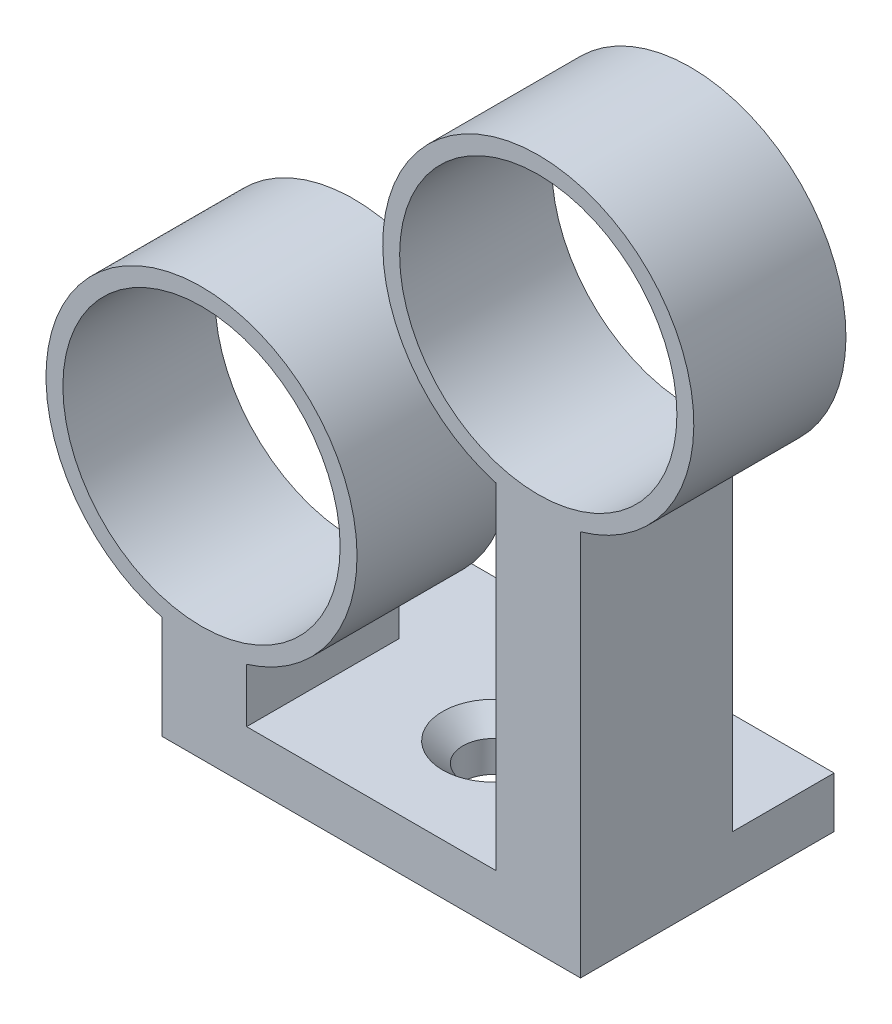
SolidWorks part; units mm, degrees
ref_plane "Alzado" through (0, 0, 0) normal (0, 0, 1) x (1, 0, 0)
ref_plane "Planta" through (0, 0, 0) normal (0, 1, 0) x (1, 0, 0)
ref_plane "Vista lateral" through (0, 0, 0) normal (1, 0, 0) x (0, 0, -1)
sketch "Sketch1" plane through (0, 0, 0) normal (0, 0, 1) x (1, 0, 0)
  line L0 (0.295, 24.8228) -> (61.4006, 24.8228) construction
  circle A0 centre (2.6252, 39.8228) radius 8.2
  circle A1 centre (22.5445, 56.5328) radius 8.2
  circle A3 centre (22.5445, 56.5328) radius 9.2
  circle A7 centre (2.6252, 39.8228) radius 9.2
  dimension "D3" = 16.4
  dimension "D5" = 16.4
  dimension "D4" = 18.4
  dimension "D1" = 18.4
  dimension "D6" = 26
  dimension "D7" = 31.71
extrude "Boss-Extrude1" add sketch "Sketch1" along normal blind 9
sketch "Sketch2" plane through (0, 0, 0) normal (0, 0, 1) x (1, 0, 0)
  line L1 (0.295, 24.8228) -> (5.295, 24.8228)
  line L2 (0.295, 24.8228) -> (0.295, 30.9228)
  line L4 (5.295, 24.8228) -> (5.295, 31.0187)
  line L7 (20.0445, 47.7228) -> (20.0445, 24.8228)
  line L8 (20.0445, 24.8228) -> (25.0445, 24.8228)
  line L9 (25.0445, 47.7228) -> (25.0445, 24.8228)
  arc A6 (20.0445, 47.7228) -> (25.0445, 47.7228) centre (22.5445, 55.5406) ccw
  arc A7 (0.295, 30.9228) -> (5.295, 31.0187) centre (2.6252, 39.8228) ccw
  dimension "D1" = 5
  dimension "D2" = 6.1
  dimension "D8" = 5
  dimension "D9" = 22.9
  dimension "D10" = 22.9
extrude "Boss-Extrude2" add sketch "Sketch2" along normal blind 9
sketch "Sketch3" plane through (0, 24.8228, 0) normal (0, -1, 0) x (1, 0, 0)
  line L1 (0.295, 9) -> (25.0445, 9)
  line L2 (0.295, 9) -> (0.295, -6)
  line L3 (0.295, -6) -> (25.0445, -6)
  line L4 (25.0445, 9) -> (25.0445, -6)
  dimension "D1" = 24.7495
  dimension "D2" = 15
extrude "Boss-Extrude3" add sketch "Sketch3" against normal blind 3
hole_wizard "Avellanado para tornillo con cabeza avellanada en cruz de M31" positions "3DSketch2" profile "Sketch5" countersink size "M3" standard "AS"
sketch3d "3DSketch2"
  point P0 (13.3121, 27.8228, 2.4258)
sketch "Sketch5" plane through (13.3121, 27.8228, 2.4258) normal (1, 0, 0) x (0, 0, 1)
  line L0 (0, 0) -> (0, 11.0815)
  line L1 (0, 11.0815) -> (1.8, 10)
  line L2 (1.8, 10) -> (1.8, 1.1588)
  line L3 (1.8, 1.1588) -> (3, 0)
  line L5 (3, 0) -> (0, 0)
  line L6 (-1.8, 1.1588) -> (-3, 0) construction
  line L10 (0, 11.0815) -> (-1.8, 10) construction
  line L11 (0, -6.35) -> (0, 107.95) construction
  dimension "Diámetro de taladro" = 3.6
  dimension "Profundidad de taladro" = 10
  dimension "Ángulo de avellanado cercano" = 6
  dimension "Ángulo de avellanado lejano" = 92
  dimension "Ángulo de perforador" = 118
